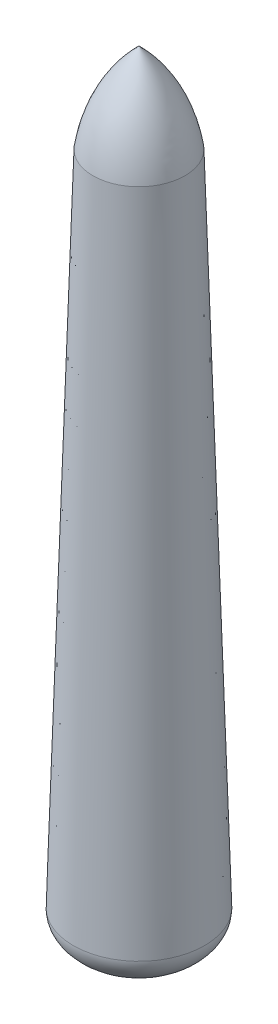
SolidWorks part; units mm, degrees
ref_plane "Front Plane" through (0, 0, 0) normal (0, 0, 1) x (1, 0, 0)
ref_plane "Top Plane" through (0, 0, 0) normal (0, 1, 0) x (1, 0, 0)
ref_plane "Right Plane" through (0, 0, 0) normal (1, 0, 0) x (0, 0, -1)
sketch "Sketch2" plane through (0, 0, 0) normal (1, 0, 0) x (0, 0, -1)
  line L0 (0, 0) -> (-50, 0)
  line L1 (-50, 0) -> (-42.5, 250)
  line L2 (-42.5, 250) -> (-7.5, 250)
  line L3 (-25, 250) -> (-25, 0)
  line L4 (-7.5, 250) -> (0, 0)
  line L5 (-25, 250) -> (-25, 299.4336)
  line L6 (-25, 0) -> (-25, -15)
  ellipse E0 centre (-25, 0) end of major axis (-50, 0) minor radius 15
  ellipse E1 centre (-25, -15) end of major axis (-32.8185, -15) minor radius 3
  spline S0 degree 2 poles (-42.5, 250) (-39.5503, 270.0241) (-25, 284.0244) knots 0 0 0 1 1 1
  point P9 (0, 0)
  point P22 (0, 0)
  point P23 (-32.7415, -14.2627)
  point P24 (0, 0)
  point P25 (-32.8185, -15)
  dimension "D1" = 250
  dimension "D2" = 50
  dimension "D3" = 35
  dimension "D4" = 15
  dimension "D5" = 3
revolve "Revolve1" add sketch "Sketch2" angle 360 about L3
